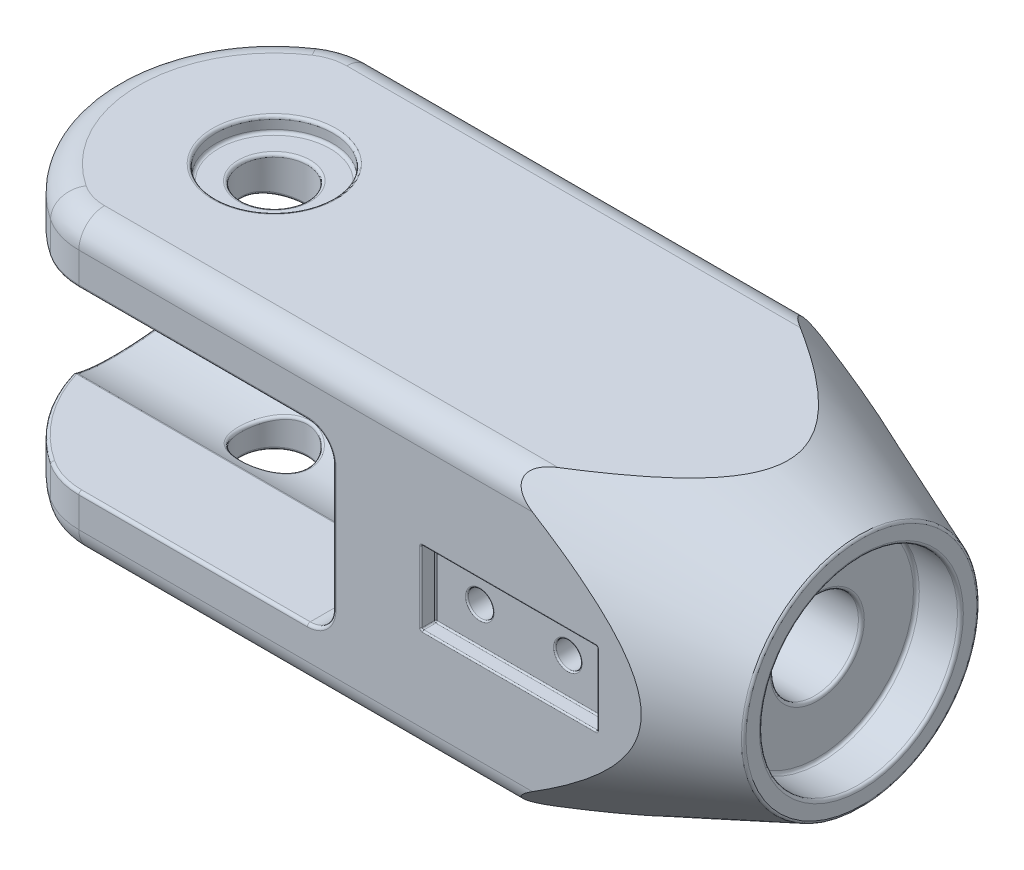
SolidWorks part; units mm, degrees
material "1060 Alloy"
ref_plane "Front Plane" through (0, 0, 0) normal (0, 0, 1) x (1, 0, 0)
ref_plane "Top Plane" through (0, 0, 0) normal (0, 1, 0) x (1, 0, 0)
ref_plane "Right Plane" through (0, 0, 0) normal (1, 0, 0) x (0, 0, -1)
sketch "Sketch1" plane through (0, 0, 0) normal (0, 1, 0) x (1, 0, 0)
  line L0 (-44.5826, 10) -> (0, 10)
  line L1 (0, 10) -> (0, -10)
  line L2 (0, -10) -> (-44.5826, -10)
  circle A1 centre (-40, 0) radius 2.25
  arc A2 (-44.5826, -10) -> (-44.5826, 10) centre (-40, 0) cw
  point P2 (0, 0)
  dimension "D3" = 4.5
  dimension "D4" = 11
  dimension "D1" = 20
  dimension "D2" = 40
extrude "Boss-Extrude1" add sketch "Sketch1" along normal mid plane 20
sketch "Sketch2" plane through (0, 0, 0) normal (0, 0, 1) x (1, 0, 0)
  line L0 (-51, 10) -> (-51, -10) construction
  line L1 (-51, 6) -> (-26, 6)
  line L2 (-51, 6) -> (-51, -6)
  line L3 (-51, -6) -> (-26, -6)
  line L4 (-26, 6) -> (-26, -6)
  line L5 (-51, 6) -> (-26, -6) construction
  line L6 (-51, -6) -> (-26, 6) construction
  point P0 (-38.5, 0)
  dimension "D1" = 12
  dimension "D2" = 26
extrude "Cut-Extrude1" cut sketch "Sketch2" against normal through all both and the other way through all
fillet "Fillet1" radius 5 4 edges at (-44.5826, -8, -10) (-44.5826, 8, -10) (-44.5826, -8, 10) (-44.5826, 8, 10)
fillet "Fillet2" radius 1.75 10 edges at (-21.6583, -10, 10) (-44.76, -10, 9.7871) (-51, -10, 0) (-44.76, -10, -9.7871) (-21.6583, 10, 10) (-44.76, 10, 9.7871) (-51, 10, 0) (-44.76, 10, -9.7871) (-21.6583, -10, -10) (-21.6583, 10, -10)
fillet "Fillet3" radius 1.75 2 edges at (-26, -6, 0) (-26, 6, 0)
sketch "Sketch3" plane through (0, 0, 0) normal (0, 0, 1) x (1, 0, 0)
  line L0 (-15, 14) -> (0, 14)
  line L1 (0, 14) -> (0, 8)
  line L2 (0, 8) -> (-15, 14)
  line L3 (0, 0) -> (22.6977, 0) construction
  line L4 (0, 8.25) -> (0, -8.25) construction
  line L5 (-5, 14) -> (-5, 10) construction
  line L6 (-43.3166, 10) -> (0, 10) construction
  dimension "D1" = 8
  dimension "D2" = 6
  dimension "D3" = 5
revolve "Cut-Revolve1" cut sketch "Sketch3" angle 360 about L3
sketch "Sketch4" plane through (0, 0, 0) normal (1, 0, 0) x (0, 0, -1)
  circle A0 centre (0, 0) radius 3
  dimension "D1" = 6
extrude "Cut-Extrude2" cut sketch "Sketch4" against normal through all
sketch "Sketch5" plane through (0, 0, 0) normal (1, 0, 0) x (0, 0, -1)
  circle A0 centre (0, 0) radius 6.75
  dimension "D1" = 13.5
extrude "Cut-Extrude3" cut sketch "Sketch5" against normal blind 3
sketch "Sketch6" plane through (-26, 0, 0) normal (-1, 0, 0) x (0, 0, 1)
  circle A1 centre (0, 0) radius 6.75
  circle A2 centre (0, 0) radius 6.75
  dimension "D1" = 0
extrude "Cut-Extrude4" cut sketch "Sketch6" along normal through all
sketch "Sketch7" plane through (-26, 0, 0) normal (-1, 0, 0) x (0, 0, 1)
  circle A1 centre (0, 0) radius 6.75
  circle A2 centre (0, 0) radius 6.75
  dimension "D1" = 0
extrude "Cut-Extrude5" cut sketch "Sketch7" against normal blind 4.5
sketch "Sketch8" plane through (0, 0, 10) normal (0, 0, 1) x (1, 0, 0)
  line L0 (-14, 0) -> (-14, -4.7539) construction
  line L1 (-20, -2.5) -> (-8, -2.5) construction
  line L2 (-20, -2.5) -> (-20, 2.5) construction
  line L3 (-20, 2.5) -> (-8, 2.5) construction
  line L4 (-8, -2.5) -> (-8, 2.5) construction
  line L5 (-20, -2.5) -> (-8, 2.5) construction
  line L6 (-20, 2.5) -> (-8, -2.5) construction
  circle A0 centre (-11, 0) radius 0.875
  circle A1 centre (-17, 0) radius 0.875
  point P0 (-14, 0)
  dimension "D3" = 1.75
  dimension "D1" = 5
  dimension "D2" = 12
  dimension "D4" = 6
  dimension "D5" = 14
extrude "Cut-Extrude6" cut sketch "Sketch8" against normal blind 6
sketch "Sketch9" plane through (0, 0, 10) normal (0, 0, 1) x (1, 0, 0)
  line L0 (-20, -2.5) -> (-20, 2.5) construction
  line L1 (-20, 2.5) -> (-8, 2.5) construction
  line L2 (-8, -2.5) -> (-8, 2.5) construction
  line L3 (-20, -2.5) -> (-8, -2.5) construction
  line L4 (-20, -2.5) -> (-20, 2.5)
  line L5 (-20, 2.5) -> (-8, 2.5)
  line L6 (-8, -2.5) -> (-8, 2.5)
  line L7 (-20, -2.5) -> (-8, -2.5)
extrude "Cut-Extrude7" cut sketch "Sketch9" against normal blind 1
fillet "Fillet4" radius 0.1 14 edges at (-14, -2.5, 10) (-14, 2.5, 10) (-20, 2.5, 9.5) (-20, -2.5, 9.5) (-20, 0, 10) (-16.125, 0, 9) (-10.125, 0, 9) (-20, 0, 9) (-14, 2.5, 9) (-14, -2.5, 9) (-8, -2.5, 9.5) (-8, 0, 9) (-8, 2.5, 9.5) (-8, 0, 10)
sketch "Sketch10" plane through (0, 10, 0) normal (0, 1, 0) x (1, 0, 0)
  circle A0 centre (-40, 0) radius 4
  dimension "D1" = 8
extrude "Cut-Extrude8" cut sketch "Sketch10" against normal blind 1
sketch "Sketch11" plane through (0, -10, 0) normal (0, -1, 0) x (1, 0, 0)
  circle A0 centre (-40, 0) radius 5
  dimension "D1" = 10
extrude "Cut-Extrude9" cut sketch "Sketch11" against normal blind 1.5
fillet "Fillet5" radius 0.2 44 edges at (-26, 0, -10) (-26, 0, 10) (-35.5333, 6, -10) (-35.5333, 6, 10) (-26.5126, -5.4874, 10) (-26.5126, -5.4874, -10) (-26.5126, 5.4874, 10) (-26.5126, 5.4874, -10) (0, 0, 8) (0, 0, -6.75) (-3, 0, -6.75) (-3, 0, -3) (-27.1155, 5.8809, -3.3132) (-26.946, 5.8044, 3.4456) (-48.8556, 6, 6.5253) (-48.8556, -6, -6.5253) (-39.6155, -6.3756, 2.2169) (-39.1532, -6, 3.0923) (-27.1155, -5.8809, 3.3132) (-39.1532, 6, 3.0923) (-50.9684, 6.6983, -0.8338) (-50.9684, -6.6983, 0.8338) (-40.3845, 6.3756, 2.2169) (-39.1532, -6, -3.0923) (-39.1532, 6, -3.0923) (-26.946, -5.8044, -3.4456) (-26, 0, -6.75) (-26, 0, 6.75) (-21.5, 0, 6.75) (-21.5, 0, 3) (-40, 9, 4) (-40, 9, 2.25) (-40, 10, 4) (-40, -8.5, -5) (-40, -8.5, -2.25) (-40, -10, -5) (-48.8556, -6, 6.5253) (-35.5333, -6, -10) (-35.5333, -6, 10) (-44.76, -6, 9.7871) (-44.76, -6, -9.7871) (-48.8556, 6, -6.5253) (-44.76, 6, 9.7871) (-44.76, 6, -9.7871)
